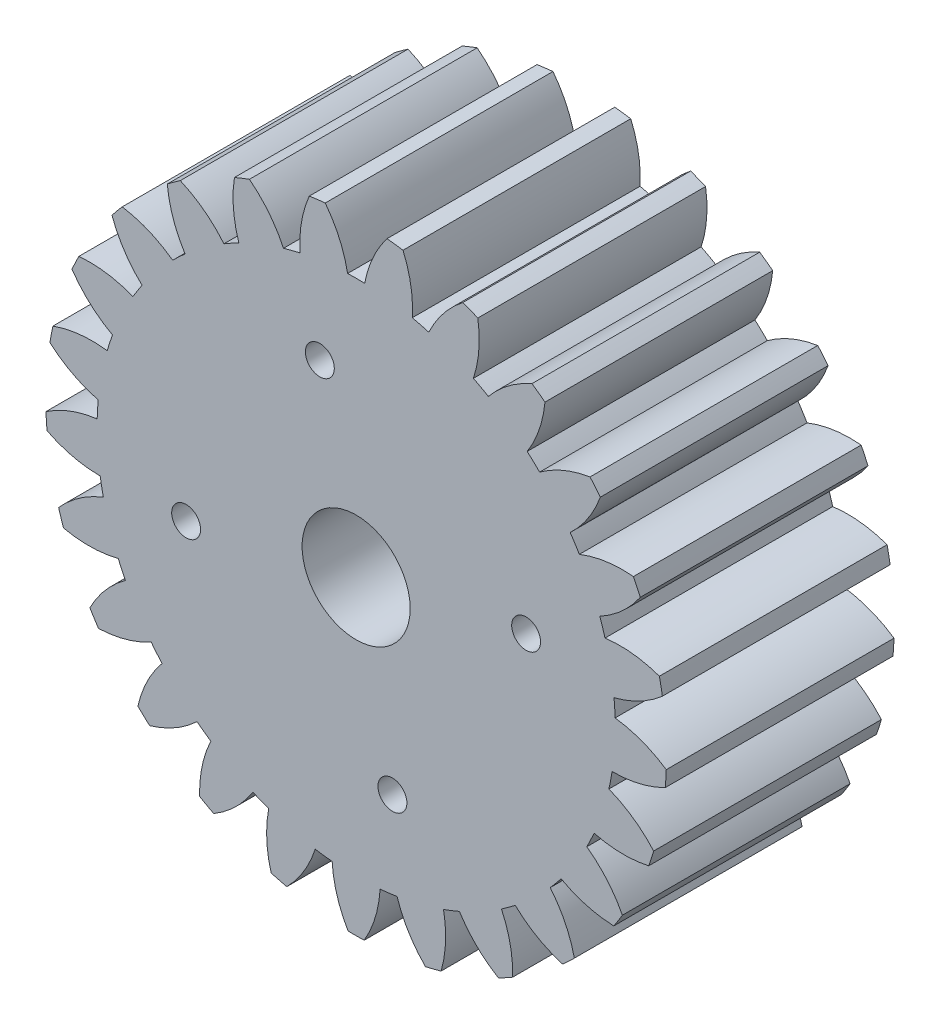
SolidWorks part; units mm, degrees
ref_plane "Front Plane" through (0, 0, 0) normal (0, 0, 1) x (1, 0, 0)
ref_plane "Top Plane" through (0, 0, 0) normal (0, 1, 0) x (1, 0, 0)
ref_plane "Right Plane" through (0, 0, 0) normal (1, 0, 0) x (0, 0, -1)
sketch "Sketch1" plane through (0, 0, 0) normal (0, 0, 1) x (1, 0, 0)
  circle A0 centre (0, 0) radius 76.397
extrude "Boss-Extrude1" add sketch "Sketch1" along normal blind 10
extrude "Cut-Extrude1" cut sketch "Sketch2" against normal through all
sketch "Sketch2" plane through (-22.988, -120.609, 58.0278) normal (0, 0, 1) x (1, 0, 0)
  circle A100 centre (28.7018, 128.515) radius 339.4013
  arc A300 (33.3877, 141.311) -> (31.8919, 139.4346) centre (36.5375, 137.2657) ccw
  arc A301 (31.8919, 139.4346) -> (31.1669, 139.6208) centre (28.7018, 128.515) ccw
  arc A302 (31.1669, 139.6208) -> (30.7601, 141.9857) centre (26.051, 139.9582) ccw
  arc A303 (30.7601, 141.9857) -> (30.0582, 142.0744) centre (28.7018, 128.515) ccw
  arc A304 (30.0582, 142.0744) -> (29.0761, 139.8849) centre (34.1151, 138.9394) ccw
  arc A305 (29.0761, 139.8849) -> (28.3276, 139.8849) centre (28.7018, 128.515) ccw
  arc A306 (28.3276, 139.8849) -> (27.3454, 142.0744) centre (23.2885, 138.9394) ccw
  arc A307 (27.3454, 142.0744) -> (26.6436, 141.9857) centre (28.7018, 128.515) ccw
  arc A308 (26.6436, 141.9857) -> (26.2367, 139.6208) centre (31.3526, 139.9582) ccw
  arc A309 (26.2367, 139.6208) -> (25.5118, 139.4346) centre (28.7018, 128.515) ccw
  arc A310 (25.5118, 139.4346) -> (24.0159, 141.311) centre (20.8661, 137.2657) ccw
  arc A311 (24.0159, 141.311) -> (23.3582, 141.0506) centre (28.7018, 128.515) ccw
  arc A312 (23.3582, 141.0506) -> (23.5523, 138.6588) centre (28.4236, 140.2579) ccw
  arc A313 (23.5523, 138.6588) -> (22.8964, 138.2982) centre (28.7018, 128.515) ccw
  arc A314 (22.8964, 138.2982) -> (20.9809, 139.7437) centre (18.9361, 135.0421) ccw
  arc A315 (20.9809, 139.7437) -> (20.4086, 139.3279) centre (28.7018, 128.515) ccw
  arc A316 (20.4086, 139.3279) -> (21.1914, 137.0595) centre (25.512, 139.8198) ccw
  arc A317 (21.1914, 137.0595) -> (20.6458, 136.5471) centre (28.7018, 128.515) ccw
  arc A318 (20.6458, 136.5471) -> (18.431, 137.4708) centre (17.6197, 132.4084) ccw
  arc A319 (18.431, 137.4708) -> (17.9801, 136.9258) centre (28.7018, 128.515) ccw
  arc A320 (17.9801, 136.9258) -> (19.3025, 134.9233) centre (22.8008, 138.6713) ccw
  arc A321 (19.3025, 134.9233) -> (18.9014, 134.2913) centre (28.7018, 128.515) ccw
  arc A322 (18.9014, 134.2913) -> (16.5265, 134.6352) centre (16.9996, 129.5301) ccw
  arc A323 (16.5265, 134.6352) -> (16.2253, 133.9951) centre (28.7018, 128.515) ccw
  arc A324 (16.2253, 133.9951) -> (18.0041, 132.3845) centre (20.4604, 136.8847) ccw
  arc A325 (18.0041, 132.3845) -> (17.7728, 131.6726) centre (28.7018, 128.515) ccw
  arc A326 (17.7728, 131.6726) -> (15.387, 131.4151) centre (17.1148, 126.588) ccw
  arc A327 (15.387, 131.4151) -> (15.2544, 130.7202) centre (28.7018, 128.515) ccw
  arc A328 (15.2544, 130.7202) -> (17.3779, 129.6025) centre (18.6379, 134.5722) ccw
  arc A329 (17.3779, 129.6025) -> (17.3309, 128.8554) centre (28.7018, 128.515) ccw
  arc A330 (17.3309, 128.8554) -> (15.0841, 128.0127) centre (17.9581, 123.767) ccw
  arc A331 (15.0841, 128.0127) -> (15.1285, 127.3067) centre (28.7018, 128.515) ccw
  arc A332 (15.1285, 127.3067) -> (17.4632, 126.7522) centre (17.4477, 131.8791) ccw
  arc A333 (17.4632, 126.7522) -> (17.6035, 126.0169) centre (28.7018, 128.515) ccw
  arc A334 (17.6035, 126.0169) -> (15.6368, 124.6419) centre (19.4764, 121.2443) ccw
  arc A335 (15.6368, 124.6419) -> (15.8554, 123.9691) centre (28.7018, 128.515) ccw
  arc A336 (15.8554, 123.9691) -> (18.2547, 124.0126) centre (16.9647, 128.9747) ccw
  arc A337 (18.2547, 124.0126) -> (18.5734, 123.3354) centre (28.7018, 128.515) ccw
  arc A338 (18.5734, 123.3354) -> (17.0105, 121.5144) centre (21.5744, 119.1784) ccw
  arc A339 (17.0105, 121.5144) -> (17.3896, 120.9172) centre (28.7018, 128.515) ccw
  arc A340 (17.3896, 120.9172) -> (19.7026, 121.556) centre (17.2191, 126.0413) ccw
  arc A341 (19.7026, 121.556) -> (20.1798, 120.9793) centre (28.7018, 128.515) ccw
  arc A342 (20.1798, 120.9793) -> (19.1188, 118.8269) centre (24.1203, 117.6992) ccw
  arc A343 (19.1188, 118.8269) -> (19.6345, 118.3426) centre (28.7018, 128.515) ccw
  arc A344 (19.6345, 118.3426) -> (21.716, 119.5366) centre (18.195, 123.2634) ccw
  arc A345 (21.716, 119.5366) -> (22.3216, 119.0967) centre (28.7018, 128.515) ccw
  arc A346 (22.3216, 119.0967) -> (21.8292, 116.748) centre (26.954, 116.8997) ccw
  arc A347 (21.8292, 116.748) -> (22.4491, 116.4072) centre (28.7018, 128.515) ccw
  arc A348 (22.4491, 116.4072) -> (24.1683, 118.0814) centre (19.8312, 120.8155) ccw
  arc A349 (24.1683, 118.0814) -> (24.8643, 117.8059) centre (28.7018, 128.515) ccw
  arc A350 (24.8643, 117.8059) -> (24.9715, 115.4086) centre (29.8975, 116.8299) ccw
  arc A351 (24.9715, 115.4086) -> (25.6566, 115.2326) centre (28.7018, 128.515) ccw
  arc A352 (25.6566, 115.2326) -> (26.9055, 117.2818) centre (22.0246, 118.8513) ccw
  arc A353 (26.9055, 117.2818) -> (27.6481, 117.1879) centre (28.7018, 128.515) ccw
  arc A354 (27.6481, 117.1879) -> (28.3481, 114.8926) centre (32.7659, 117.4944) ccw
  arc A355 (28.3481, 114.8926) -> (29.0555, 114.8926) centre (28.7018, 128.515) ccw
  arc A356 (29.0555, 114.8926) -> (29.7555, 117.1879) centre (24.6377, 117.4944) ccw
  arc A357 (29.7555, 117.1879) -> (30.4981, 117.2818) centre (28.7018, 128.515) ccw
  arc A358 (30.4981, 117.2818) -> (31.747, 115.2326) centre (35.379, 118.8513) ccw
  arc A359 (31.747, 115.2326) -> (32.4322, 115.4086) centre (28.7018, 128.515) ccw
  arc A360 (32.4322, 115.4086) -> (32.5394, 117.8059) centre (27.5061, 116.8299) ccw
  arc A361 (32.5394, 117.8059) -> (33.2353, 118.0814) centre (28.7018, 128.515) ccw
  arc A362 (33.2353, 118.0814) -> (34.9545, 116.4072) centre (37.5725, 120.8155) ccw
  arc A363 (34.9545, 116.4072) -> (35.5744, 116.748) centre (28.7018, 128.515) ccw
  arc A364 (35.5744, 116.748) -> (35.0821, 119.0967) centre (30.4496, 116.8997) ccw
  arc A365 (35.0821, 119.0967) -> (35.6876, 119.5366) centre (28.7018, 128.515) ccw
  arc A366 (35.6876, 119.5366) -> (37.7692, 118.3426) centre (39.2086, 123.2634) ccw
  arc A367 (37.7692, 118.3426) -> (38.2848, 118.8269) centre (28.7018, 128.515) ccw
  arc A368 (38.2848, 118.8269) -> (37.2239, 120.9793) centre (33.2834, 117.6992) ccw
  arc A369 (37.2239, 120.9793) -> (37.701, 121.556) centre (28.7018, 128.515) ccw
  arc A370 (37.701, 121.556) -> (40.0141, 120.9172) centre (40.1845, 126.0413) ccw
  arc A371 (40.0141, 120.9172) -> (40.3931, 121.5144) centre (28.7018, 128.515) ccw
  arc A372 (40.3931, 121.5144) -> (38.8302, 123.3354) centre (35.8292, 119.1784) ccw
  arc A373 (38.8302, 123.3354) -> (39.1489, 124.0126) centre (28.7018, 128.515) ccw
  arc A374 (39.1489, 124.0126) -> (41.5482, 123.9691) centre (40.439, 128.9747) ccw
  arc A375 (41.5482, 123.9691) -> (41.7668, 124.6419) centre (28.7018, 128.515) ccw
  arc A376 (41.7668, 124.6419) -> (39.8001, 126.0169) centre (37.9272, 121.2443) ccw
  arc A377 (39.8001, 126.0169) -> (39.9404, 126.7522) centre (28.7018, 128.515) ccw
  arc A378 (39.9404, 126.7522) -> (42.2751, 127.3067) centre (39.9559, 131.8791) ccw
  arc A379 (42.2751, 127.3067) -> (42.3195, 128.0127) centre (28.7018, 128.515) ccw
  arc A380 (42.3195, 128.0127) -> (40.0727, 128.8554) centre (39.4455, 123.767) ccw
  arc A381 (40.0727, 128.8554) -> (40.0257, 129.6025) centre (28.7018, 128.515) ccw
  arc A382 (40.0257, 129.6025) -> (42.1492, 130.7202) centre (38.7657, 134.5722) ccw
  arc A383 (42.1492, 130.7202) -> (42.0167, 131.4151) centre (28.7018, 128.515) ccw
  arc A384 (42.0167, 131.4151) -> (39.6308, 131.6726) centre (40.2888, 126.588) ccw
  arc A385 (39.6308, 131.6726) -> (39.3995, 132.3845) centre (28.7018, 128.515) ccw
  arc A386 (39.3995, 132.3845) -> (41.1783, 133.9951) centre (36.9432, 136.8847) ccw
  arc A387 (41.1783, 133.9951) -> (40.8771, 134.6352) centre (28.7018, 128.515) ccw
  arc A388 (40.8771, 134.6352) -> (38.5022, 134.2913) centre (40.404, 129.5301) ccw
  arc A389 (38.5022, 134.2913) -> (38.1012, 134.9233) centre (28.7018, 128.515) ccw
  arc A390 (38.1012, 134.9233) -> (39.4235, 136.9258) centre (34.6028, 138.6713) ccw
  arc A391 (39.4235, 136.9258) -> (38.9726, 137.4708) centre (28.7018, 128.515) ccw
  arc A392 (38.9726, 137.4708) -> (36.7578, 136.5471) centre (39.7839, 132.4084) ccw
  arc A393 (36.7578, 136.5471) -> (36.2122, 137.0595) centre (28.7018, 128.515) ccw
  arc A394 (36.2122, 137.0595) -> (36.995, 139.3279) centre (31.8917, 139.8198) ccw
  arc A395 (36.995, 139.3279) -> (36.4227, 139.7437) centre (28.7018, 128.515) ccw
  arc A396 (36.4227, 139.7437) -> (34.5072, 138.2982) centre (38.4675, 135.0421) ccw
  arc A397 (34.5072, 138.2982) -> (33.8513, 138.6588) centre (28.7018, 128.515) ccw
  arc A398 (33.8513, 138.6588) -> (34.0454, 141.0506) centre (28.9801, 140.2579) ccw
  arc A399 (34.0454, 141.0506) -> (33.3877, 141.311) centre (28.7018, 128.515) ccw
extrude "Cut-Extrude2" cut sketch "Sketch3" against normal through all both and the other way through all
sketch "Sketch3" plane through (-22.988, -120.609, 52.0278) normal (0, 0, -1) x (-1, 0, 0)
  circle A3 centre (-28.7018, 128.515) radius 2.373
  circle A10 centre (-21.2373, 126.9216) radius 0.635
  circle A13 centre (-27.1083, 135.9796) radius 0.635
  circle A16 centre (-36.1663, 130.1085) radius 0.635
  circle A19 centre (-30.2953, 121.0505) radius 0.635
